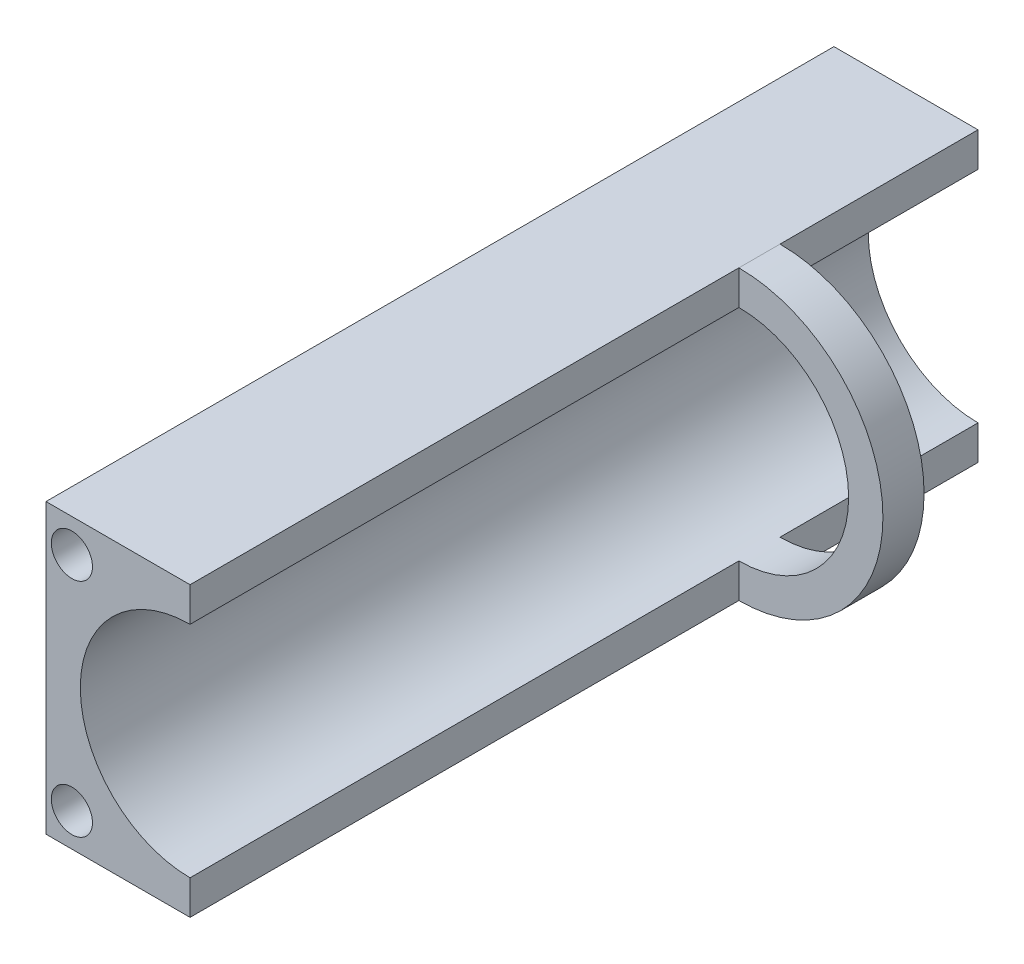
SolidWorks part; units mm, degrees
ref_plane "Front Plane" through (0, 0, 0) normal (0, 0, 1) x (1, 0, 0)
ref_plane "Top Plane" through (0, 0, 0) normal (0, 1, 0) x (1, 0, 0)
ref_plane "Right Plane" through (0, 0, 0) normal (1, 0, 0) x (0, 0, -1)
sketch "Sketch1" plane through (0, 0, 0) normal (0, 0, 1) x (1, 0, 0)
  line L0 (0, -8) -> (0, -10.5)
  line L1 (0, 10.5) -> (0, 8)
  line L2 (0, 10.5) -> (-10.5, 10.5)
  line L3 (-10.5, 10.5) -> (-10.5, -10.5)
  line L4 (-10.5, -10.5) -> (0, -10.5)
  arc A1 (0, 8) -> (0, -8) centre (0, 0) ccw
  point P3 (0, 10.5)
  point P4 (0, -10.5)
  dimension "D1" = 10.5
  dimension "D2" = 8
extrude "Boss-Extrude1" add sketch "Sketch1" along normal blind 57.43
sketch "Sketch2" plane through (0, 0, 0) normal (1, 0, 0) x (0, 0, -1)
  line L0 (-14.43, -10.5) -> (-17.43, -10.5)
  line L1 (-14.43, -10.5) -> (-14.43, -8)
  line L2 (-17.43, -10.5) -> (-17.43, -8)
  line L3 (-14.43, -8) -> (-17.43, -8)
  line L4 (-57.43, -10.5) -> (0, -10.5) construction
  line L5 (-57.43, -8) -> (-57.43, -10.5) construction
  line L6 (0, 0) -> (-50.7466, 0) construction
  line L7 (-57.43, -8) -> (0, -8) construction
  point P13 (-57.43, -9.25)
  dimension "D1" = 40
  dimension "D2" = 3
revolve "Revolve1" add sketch "Sketch2" angle 360 about L6
sketch "Sketch6" plane through (0, 0, 57.43) normal (0, 0, 1) x (1, 0, 0)
  circle A2 centre (-8.6133, 8.08) radius 1.5
  circle A3 centre (-8.6133, -8.08) radius 1.5
  point P0 (-8.6133, 8.08)
  point P1 (-8.6133, -8.08)
  point P3 (0, 0)
  point P5 (0, 0)
  point P6 (-3.5341, 15.4739)
  point P9 (-3.1925, 4.249)
  dimension "D1" = 16.16
  dimension "D2" = 11.81
  dimension "D3" = 11.81
extrude "Cut-Extrude1" cut sketch "Sketch6" against normal blind 0.1
sketch "Sketch9" plane through (0, 0, 0) normal (0, 0, -1) x (-1, 0, 0)
  circle A1 centre (8.6133, 8.08) radius 1.5
  circle A2 centre (8.6133, -8.08) radius 1.5
  point P0 (0, 0)
  point P3 (0, 0)
  dimension "D1" = 16.16
  dimension "D2" = 11.81
  dimension "D5" = 11.81
extrude "Cut-Extrude2" cut sketch "Sketch9" against normal blind 0.1
hole_wizard "Ø3.0mm Dowel Hole1" positions "Sketch12" profile "Sketch13" hole size "Ø3.0" standard "ANSI Metric"
sketch "Sketch12" plane through (0, 0, 57.43) normal (0, 0, 1) x (1, 0, 0)
  point P0 (-8.6133, 8.08)
  point P3 (-8.6133, -8.08)
sketch "Sketch13" plane through (-8.6133, 8.08, 57.43) normal (1, 0, 0) x (0, -1, 0)
  line L0 (0, 0) -> (0, 3.9013)
  line L1 (0, 3.9013) -> (1.5, 3)
  line L2 (1.5, 3) -> (1.5, 0)
  line L5 (1.5, 0) -> (0, 0)
  line L10 (0, 3.9013) -> (-1.5, 3) construction
  line L11 (0, -6.35) -> (0, 107.95) construction
  dimension "Hole Dia." = 3
  dimension "Hole Depth" = 3
  dimension "Drill Angle" = 118
hole_wizard "Ø3.0mm Dowel Hole2" positions "Sketch14" profile "Sketch15" hole size "Ø3.0" standard "ANSI Metric"
sketch "Sketch14" plane through (0, 0, 0) normal (0, 0, -1) x (-1, 0, 0)
  point P0 (8.6133, 8.08)
  point P3 (8.6133, -8.08)
sketch "Sketch15" plane through (-8.6133, 8.08, 0) normal (1, 0, 0) x (0, 1, 0)
  line L0 (0, 0) -> (0, 3.9013)
  line L1 (0, 3.9013) -> (1.5, 3)
  line L2 (1.5, 3) -> (1.5, 0)
  line L5 (1.5, 0) -> (0, 0)
  line L10 (0, 3.9013) -> (-1.5, 3) construction
  line L11 (0, -6.35) -> (0, 107.95) construction
  dimension "Hole Dia." = 3
  dimension "Hole Depth" = 3
  dimension "Drill Angle" = 118
